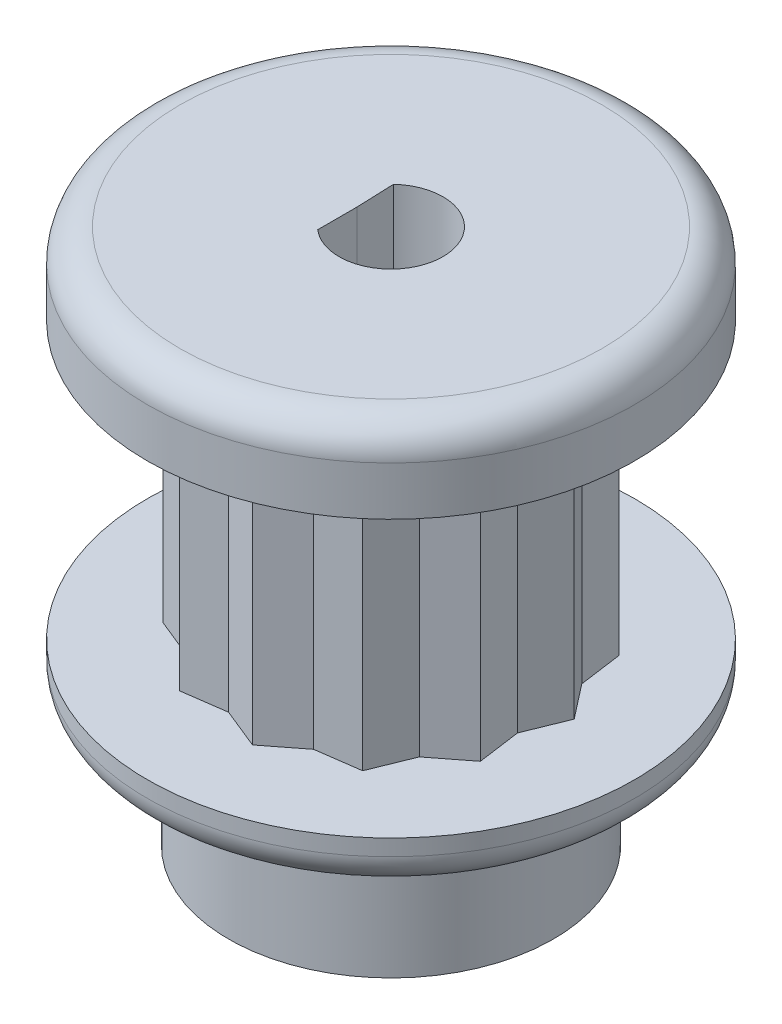
SolidWorks part; units mm, degrees
ref_plane "Plan de face" through (0, 0, 0) normal (0, 0, 1) x (1, 0, 0)
ref_plane "Plan de dessus" through (0, 0, 0) normal (0, 1, 0) x (1, 0, 0)
ref_plane "Plan de droite" through (0, 0, 0) normal (1, 0, 0) x (0, 0, -1)
sketch "Esquisse1" plane through (0, 0, 0) normal (0, 1, 0) x (1, 0, 0)
  line L0 (0.5534, 4.4486) -> (-0.688, 4.9524)
  line L1 (4.633, -1.8804) -> (4.4486, -0.5534)
  line L2 (3.9449, 3.0721) -> (2.7035, 3.5759)
  line L3 (-0.688, 4.9524) -> (-1.7451, 4.1293)
  line L4 (-4.633, 1.8804) -> (-4.4486, 0.5534)
  line L5 (-3.9449, -3.0721) -> (-2.7035, -3.5759)
  line L6 (0.688, -4.9524) -> (1.7451, -4.1293)
  line L7 (3.0721, -3.9449) -> (3.5759, -2.7035)
  line L8 (4.9524, 0.688) -> (4.1293, 1.7451)
  line L9 (1.8804, 4.633) -> (0.5534, 4.4486)
  line L10 (-3.0721, 3.9449) -> (-3.5759, 2.7035)
  line L11 (-4.9524, -0.688) -> (-4.1293, -1.7451)
  line L12 (-1.8804, -4.633) -> (-0.5534, -4.4486)
  line L13 (2.7035, 3.5759) -> (1.8804, 4.633)
  line L14 (4.1293, 1.7451) -> (3.9449, 3.0721)
  line L15 (4.4486, -0.5534) -> (4.9524, 0.688)
  line L16 (-1.7451, 4.1293) -> (-3.0721, 3.9449)
  line L17 (-4.4486, 0.5534) -> (-4.9524, -0.688)
  line L18 (-3.5759, 2.7035) -> (-4.633, 1.8804)
  line L19 (-4.1293, -1.7451) -> (-3.9449, -3.0721)
  line L20 (-2.7035, -3.5759) -> (-1.8804, -4.633)
  line L21 (-0.5534, -4.4486) -> (0.688, -4.9524)
  line L22 (1.7451, -4.1293) -> (3.0721, -3.9449)
  line L23 (3.5759, -2.7035) -> (4.633, -1.8804)
extrude "Boss.-Extru.2" add sketch "Esquisse1" along normal blind 8.5
sketch "Esquisse2" plane through (0, 8.5, 0) normal (0, 1, 0) x (1, 0, 0)
  circle A0 centre (0, 0) radius 7.5
extrude "Boss.-Extru.3" add sketch "Esquisse2" along normal blind 2.5
sketch "Esquisse3" plane through (0, 0, 0) normal (0, -1, 0) x (1, 0, 0)
  circle A0 centre (0, 0) radius 7.5
extrude "Boss.-Extru.4" add sketch "Esquisse3" along normal blind 1.5
sketch "Esquisse4" plane through (0, -1.5, 0) normal (0, -1, 0) x (1, 0, 0)
  circle A0 centre (0, 0) radius 5
extrude "Boss.-Extru.5" add sketch "Esquisse4" along normal blind 4
sketch "Esquisse6" plane through (0, -5.5, 0) normal (0, -1, 0) x (1, 0, 0)
  circle A0 centre (0, 0) radius 3
extrude "Enlèv. mat.-Extru.2" cut sketch "Esquisse6" against normal blind 0.1
fillet "Congé4" radius 1 2 edges at (0, -1.5, -7.5) (0, 11, 7.5)
sketch "Esquisse7" plane through (0, -5.4, 0) normal (0, -1, 0) x (1, 0, 0)
  line L0 (1.6, 0) -> (-1.0483, 0) construction
  line L1 (-1.0483, 0) -> (-1.0924, -1.169)
  line L2 (-1.0483, 0) -> (-1.0483, 1.2088)
  arc A0 (-1.0924, -1.169) -> (-1.0483, 1.2088) centre (0, 0) ccw
extrude "Enlèv. mat.-Extru.3" cut sketch "Esquisse7" against normal through all
